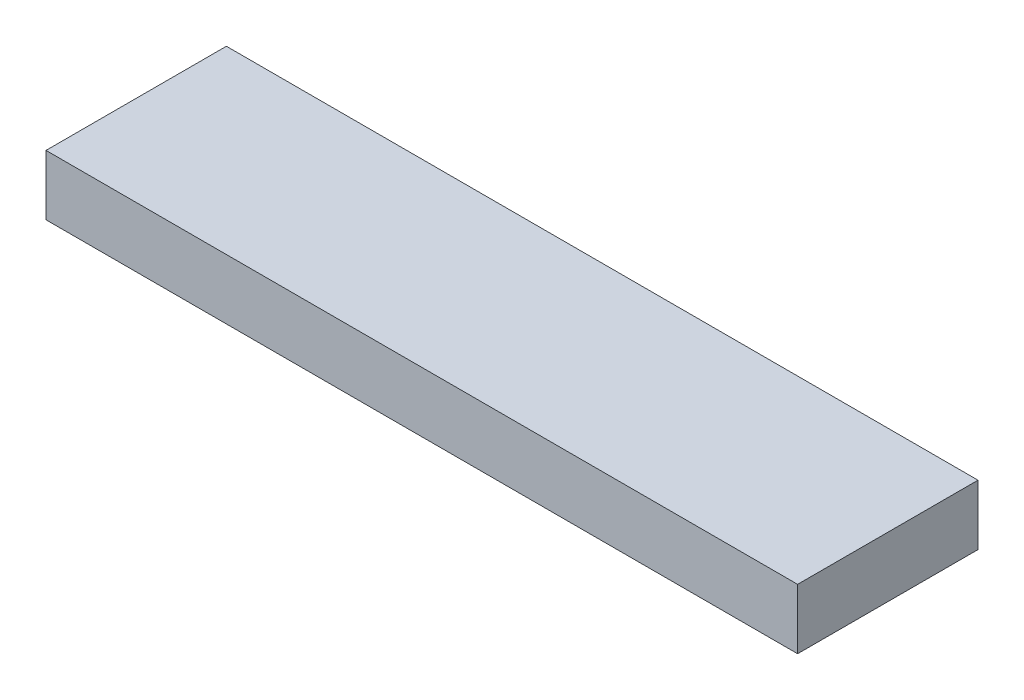
SolidWorks part; units mm, degrees
material "1023 Carbon Steel Sheet (SS)"
ref_plane "Front Plane" through (0, 0, 0) normal (0, 0, 1) x (1, 0, 0)
ref_plane "Top Plane" through (0, 0, 0) normal (0, 1, 0) x (1, 0, 0)
ref_plane "Right Plane" through (0, 0, 0) normal (1, 0, 0) x (0, 0, -1)
sketch "Sketch1" plane through (0, 0, 0) normal (0, 1, 0) x (1, 0, 0)
  line L1 (0, 0) -> (50, 0)
  line L2 (0, 0) -> (0, 12)
  line L3 (0, 12) -> (50, 12)
  line L4 (50, 0) -> (50, 12)
  dimension "D1" = 12
  dimension "D2" = 50
extrude "Boss-Extrude1" add sketch "Sketch1" along normal blind 4
